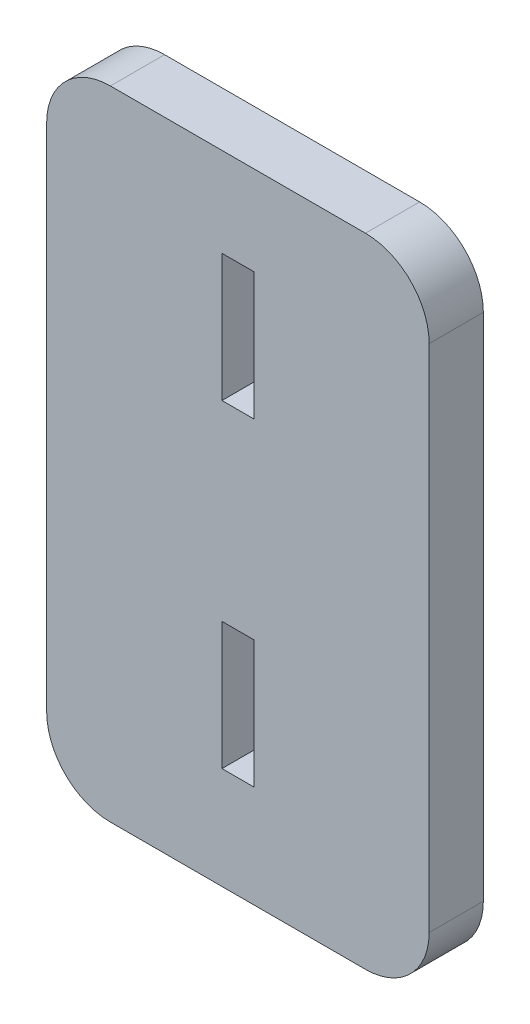
SolidWorks part; units mm, degrees
ref_plane "Alzado" through (0, 0, 0) normal (0, 0, 1) x (1, 0, 0)
ref_plane "Planta" through (0, 0, 0) normal (0, 1, 0) x (1, 0, 0)
ref_plane "Vista lateral" through (0, 0, 0) normal (1, 0, 0) x (0, 0, -1)
sketch "Croquis2" plane through (0, 0, 0) normal (0, 0, 1) x (1, 0, 0)
  line L0 (50, 50) -> (50, -50) construction
  line L1 (-30, 50) -> (30, 50)
  line L2 (-30, 50) -> (-30, -50)
  line L3 (-30, -50) -> (30, -50)
  line L4 (30, 50) -> (30, -50)
  line L5 (-30, 50) -> (30, -50) construction
  line L6 (-30, -50) -> (30, 50) construction
  line L7 (0, 50) -> (0, -50) construction
  line L8 (-50, 50) -> (-50, -50) construction
  point P0 (0, 0)
  dimension "D1" = 100
  dimension "D2" = 60
  dimension "D3" = 80
  dimension "D4" = 80
extrude "Saliente-Extruir1" add sketch "Croquis2" along normal blind 8.5
ref_plane "Plano1" through (0, 0, 8.5) normal (0, 0, 1) x (1, 0, 0)
sketch "Croquis4" plane through (0, 0, 8.5) normal (0, 0, 1) x (1, 0, 0)
  line L0 (0, 50) -> (0, -50) construction
  line L1 (30, 50) -> (-30, 50) construction
  line L2 (-30, -50) -> (30, -50) construction
  line L4 (-30, 50) -> (-30, -50) construction
  line L5 (30, -50) -> (30, 50) construction
  line L6 (-30, 0) -> (30, 0) construction
  line L8 (-2.5, 36.02) -> (2.5, 36.02)
  line L9 (-2.5, 36.02) -> (-2.5, 16.02)
  line L10 (-2.5, 16.02) -> (2.5, 16.02)
  line L11 (2.5, 36.02) -> (2.5, 16.02)
  line L12 (-2.5, 36.02) -> (2.5, 16.02) construction
  line L13 (-2.5, 16.02) -> (2.5, 36.02) construction
  line L14 (-2.5, -13.98) -> (2.5, -13.98)
  line L15 (-2.5, -13.98) -> (-2.5, -33.98)
  line L16 (-2.5, -33.98) -> (2.5, -33.98)
  line L17 (2.5, -13.98) -> (2.5, -33.98)
  line L18 (-2.5, -13.98) -> (2.5, -33.98) construction
  line L19 (-2.5, -33.98) -> (2.5, -13.98) construction
  point P2 (0, 0)
  point P14 (0, 26.02)
  point P19 (0, -23.98)
  point P24 (8, 40)
  point P29 (8, -40)
  dimension "D1" = 23.98
  dimension "D2" = 26.02
  dimension "D3" = 5
  dimension "D4" = 20
  dimension "D7" = 5
  dimension "D8" = 20
extrude "Cortar-Extruir1" cut sketch "Croquis4" against normal blind 7.48
fillet "Redondeo1" radius 10 1 edges at (-30, 50, 4.25)
fillet "Redondeo2" radius 10 3 edges at (30, -50, 4.25) (-30, -50, 4.25) (30, 50, 4.25)
